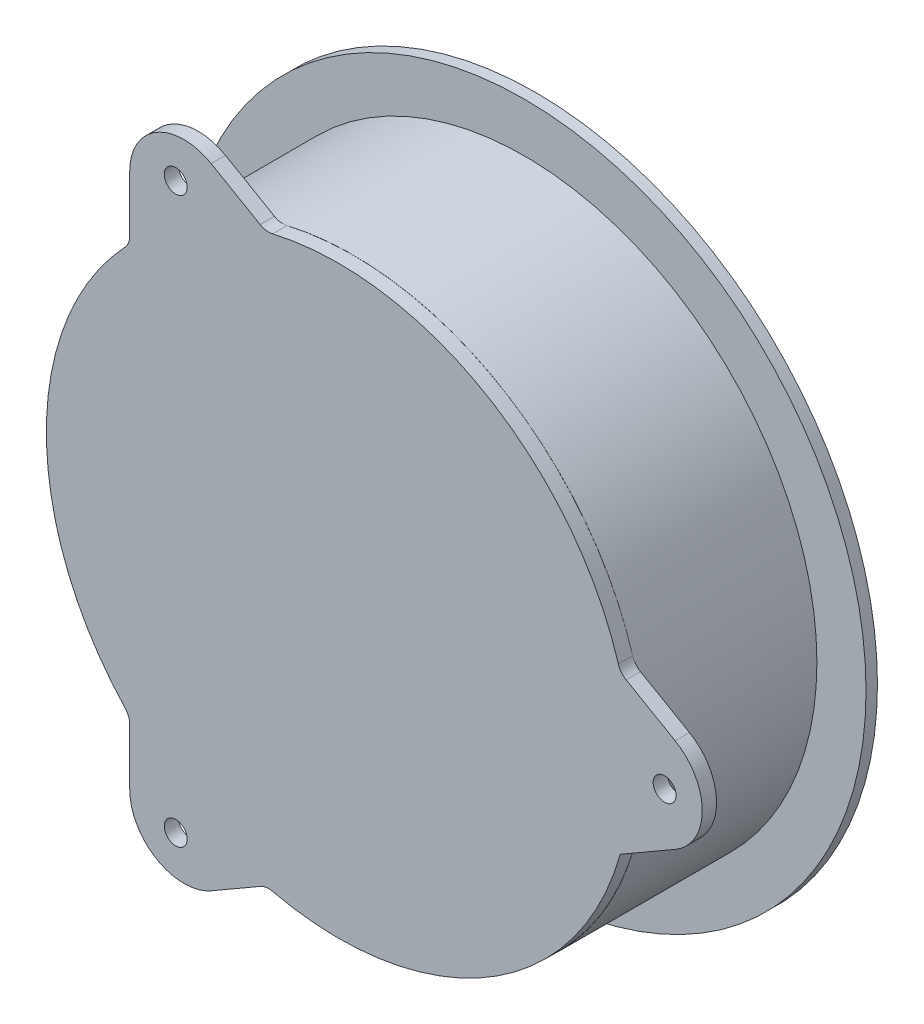
SolidWorks part; units mm, degrees
ref_plane "Front Plane" through (0, 0, 0) normal (0, 0, 1) x (1, 0, 0)
ref_plane "Top Plane" through (0, 0, 0) normal (0, 1, 0) x (1, 0, 0)
ref_plane "Right Plane" through (0, 0, 0) normal (1, 0, 0) x (0, 0, -1)
ref_plane "Plane2" through (0, 0, 0) normal (0, 0, 1) x (1, 0, 0)
sketch "Sketch4" plane through (0, 0, 0) normal (0, 0, 1) x (1, 0, 0)
  circle A0 centre (0, 0) radius 151.84
  circle A1 centre (0, 0) radius 128.3759
extrude "Extrude1" add sketch "Sketch4" along normal blind 5.08
ref_plane "Plane3" through (0, 0, 5.08) normal (0, 0, 1) x (1, 0, 0)
sketch "Sketch6" plane through (0, 0, 5.08) normal (0, 0, 1) x (1, 0, 0)
  circle A0 centre (0, 0) radius 129.9998
  circle A1 centre (0, 0) radius 124.8548
extrude "Extrude2" add sketch "Sketch6" along normal blind 76.2
ref_plane "Plane4" through (0, 0, 81.28) normal (0, 0, 1) x (1, 0, 0)
sketch "Sketch8" plane through (0, 0, 81.28) normal (0, 0, 1) x (1, 0, 0)
  line L0 (-92.8694, -93.932) -> (-92.8694, -119.0601)
  line L1 (-80.8044, 139.9573) -> (-72.4329, 125.4574) construction
  line L4 (-56.6744, -139.9573) -> (-34.9128, -127.3932)
  line L5 (125.1351, -34.9895) -> (149.5437, -20.8972)
  line L9 (149.5437, 20.8972) -> (127.7822, 33.4612)
  line L10 (-34.9128, 127.3932) -> (-56.6744, 139.9573)
  line L11 (-92.8694, 119.0601) -> (-92.8694, 93.932)
  circle A0 centre (-72.4329, 125.4574) radius 5.0996
  circle A1 centre (144.8658, 0) radius 5.0996
  circle A2 centre (-72.4329, -125.4574) radius 5.0996
  arc A15 (-92.8694, -119.0601) -> (-56.6744, -139.9573) centre (-68.7394, -119.0601) ccw
  arc A16 (-29.3798, -126.5697) -> (-34.9128, -127.3932) centre (-31.1028, -133.9923) ccw
  arc A17 (-29.3798, -126.5697) -> (125.1351, -34.9895) centre (0, 0) ccw
  arc A18 (149.5437, -20.8972) -> (149.5437, 20.8972) centre (137.4787, 0) ccw
  arc A19 (127.7822, 33.4612) -> (124.3025, 37.8412) centre (131.5922, 40.0604) cw
  arc A20 (124.3025, 37.8412) -> (-29.3798, 126.5697) centre (0, 0) ccw
  arc A21 (-29.3798, 126.5697) -> (-34.9128, 127.3932) centre (-31.1028, 133.9923) cw
  arc A22 (-56.6744, 139.9573) -> (-92.8694, 119.0601) centre (-68.7394, 119.0601) ccw
  arc A23 (-94.9226, 88.7285) -> (-92.8694, 93.932) centre (-100.4894, 93.932) ccw
  arc A24 (-94.9226, 88.7285) -> (-94.9226, -88.7285) centre (0, 0) ccw
  arc A25 (-94.9226, -88.7285) -> (-92.8694, -93.932) centre (-100.4894, -93.932) cw
  point P23 (-32.9904, 120.4174)
  point P26 (-87.7894, 88.7792)
  point P29 (120.7798, 31.6382)
extrude "Extrude3" add sketch "Sketch8" along normal blind 6.35
